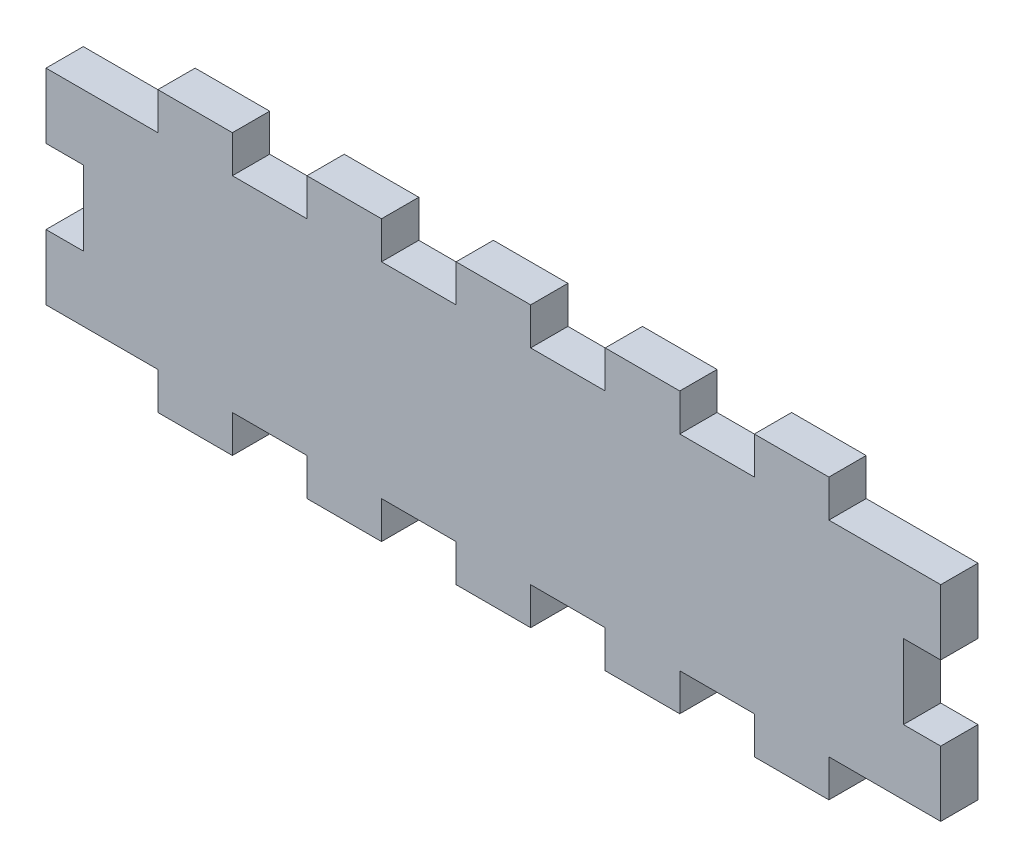
SolidWorks part; units mm, degrees
ref_plane "Front Plane" through (0, 0, 0) normal (0, 0, 1) x (1, 0, 0)
ref_plane "Top Plane" through (0, 0, 0) normal (0, 1, 0) x (1, 0, 0)
ref_plane "Right Plane" through (0, 0, 0) normal (1, 0, 0) x (0, 0, -1)
sketch "Sketch1" plane through (0, 0, 0) normal (0, 0, 1) x (1, 0, 0)
  line L1 (-76.2, -17.4625) -> (76.2, -17.4625)
  line L2 (-76.2, -17.4625) -> (-76.2, 17.4625)
  line L3 (-76.2, 17.4625) -> (76.2, 17.4625)
  line L4 (76.2, -17.4625) -> (76.2, 17.4625)
  line L5 (-76.2, -17.4625) -> (76.2, 17.4625) construction
  line L6 (-76.2, 17.4625) -> (76.2, -17.4625) construction
  point P0 (0, 0)
  dimension "D1" = 34.925
  dimension "D2" = 152.4
extrude "Mass" add sketch "Sketch1" along normal blind 6.35
sketch "Bore Pattern" plane through (0, 0, 6.35) normal (0, 0, 1) x (1, 0, 0)
  line L0 (0, 0) -> (-38.2053, 0) construction
  line L1 (0, 0) -> (38.1, 0) construction
  dimension "D1" = 38.2053
  dimension "D2" = 38.1
sketch "Sketch3" plane through (0, 0, 0) normal (0, 0, -1) x (-1, 0, 0)
  line L0 (0, 0) -> (0, 17.4625) construction
  line L2 (0, 0) -> (0, -17.4625) construction
  line L4 (76.2, -17.4625) -> (-76.2, -17.4625) construction
  line L5 (6.35, 11.1125) -> (-6.35, 11.1125)
  line L6 (6.35, 11.1125) -> (6.35, 23.8125)
  line L7 (6.35, 23.8125) -> (-6.35, 23.8125)
  line L8 (-6.35, 11.1125) -> (-6.35, 23.8125)
  line L9 (6.35, 11.1125) -> (-6.35, 23.8125) construction
  line L10 (6.35, 23.8125) -> (-6.35, 11.1125) construction
  line L11 (6.35, -23.8125) -> (-6.35, -23.8125)
  line L12 (6.35, -23.8125) -> (6.35, -11.1125)
  line L13 (6.35, -11.1125) -> (-6.35, -11.1125)
  line L14 (-6.35, -23.8125) -> (-6.35, -11.1125)
  line L15 (6.35, -23.8125) -> (-6.35, -11.1125) construction
  line L16 (6.35, -11.1125) -> (-6.35, -23.8125) construction
  line L18 (-76.2, 17.4625) -> (76.2, 17.4625) construction
  dimension "D1" = 12.7
  dimension "D2" = 12.7
extrude "Top Tooth" add sketch "Sketch3" against normal up to surface (6.35 mm away) up to face at (0, 0, 6.35)
pattern_linear "Top Puzzle" count 3 spacing 25.4 along (-1, 0, 0) count 3 spacing 25.4 along (1, 0, 0) of "Top Tooth"
sketch "Sketch4" plane through (0, 0, 6.35) normal (0, 0, 1) x (1, 0, 0)
  line L0 (0, 0) -> (76.2, 0) construction
  line L2 (76.2, -17.4625) -> (76.2, 17.4625) construction
  line L3 (0, 0) -> (-76.2, 0) construction
  line L4 (69.85, -6.35) -> (82.55, -6.35)
  line L5 (69.85, -6.35) -> (69.85, 6.35)
  line L6 (69.85, 6.35) -> (82.55, 6.35)
  line L7 (82.55, -6.35) -> (82.55, 6.35)
  line L8 (69.85, -6.35) -> (82.55, 6.35) construction
  line L9 (69.85, 6.35) -> (82.55, -6.35) construction
  line L11 (-76.2, 17.4625) -> (-76.2, -17.4625) construction
  line L13 (-69.85, -6.35) -> (-82.55, -6.35)
  line L14 (-69.85, -6.35) -> (-69.85, 6.35)
  line L15 (-69.85, 6.35) -> (-82.55, 6.35)
  line L16 (-82.55, -6.35) -> (-82.55, 6.35)
  line L17 (-69.85, -6.35) -> (-82.55, 6.35) construction
  line L18 (-69.85, 6.35) -> (-82.55, -6.35) construction
  dimension "D1" = 12.7
  dimension "D2" = 12.7
extrude "Side Tooth" cut sketch "Sketch4" against normal through all
